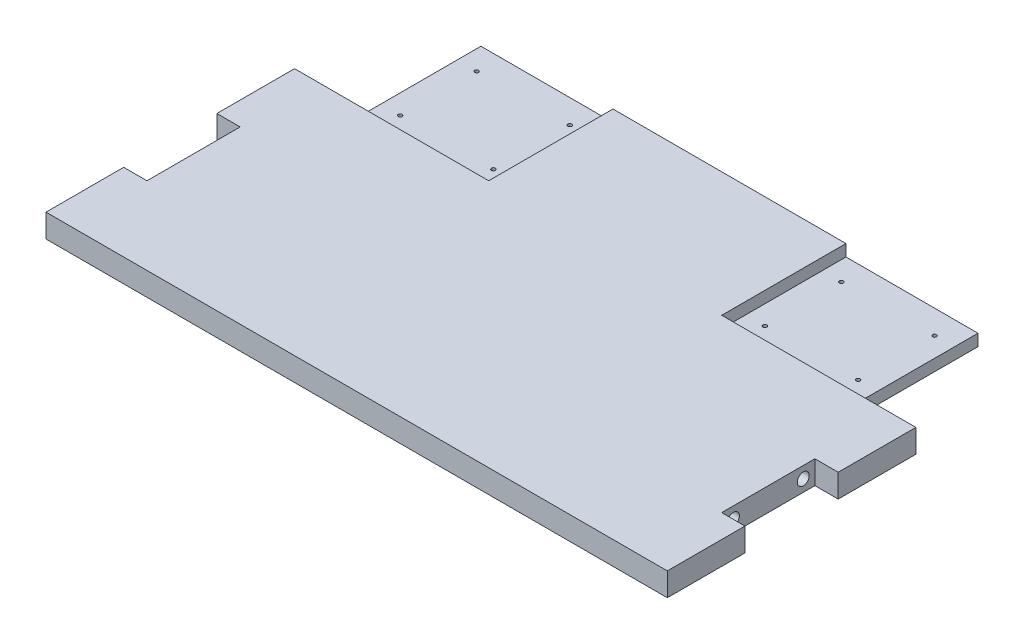
SolidWorks part; units mm, degrees
material "PE High Density"
ref_plane "Front Plane" through (0, 0, 0) normal (0, 0, 1) x (1, 0, 0)
ref_plane "Top Plane" through (0, 0, 0) normal (0, 1, 0) x (1, 0, 0)
ref_plane "Right Plane" through (0, 0, 0) normal (1, 0, 0) x (0, 0, -1)
sketch "Sketch1" plane through (0, 0, 0) normal (0, 1, 0) x (1, 0, 0)
  line L1 (-127, 127) -> (127, 127)
  line L2 (-127, 127) -> (-127, -127)
  line L3 (-127, -127) -> (127, -127)
  line L4 (127, 127) -> (127, -127)
  line L5 (-127, 127) -> (127, -127) construction
  line L6 (-127, -127) -> (127, 127) construction
  point P0 (0, 0)
  dimension "D1" = 254
  dimension "D2" = 254
extrude "Boss-Extrude1" add sketch "Sketch1" along normal blind 9.525
sketch "Sketch2" plane through (0, 9.525, 0) normal (0, 1, 0) x (1, 0, 0)
  line L0 (0, 0) -> (0, 151.7157) construction
  line L1 (-127, 127) -> (-101.6, 127)
  line L2 (-127, 127) -> (-127, 76.2)
  line L3 (-127, 76.2) -> (-101.6, 76.2)
  line L4 (-101.6, 127) -> (-101.6, 76.2)
  line L5 (127, 76.2) -> (101.6, 76.2)
  line L6 (127, 127) -> (127, 76.2)
  line L7 (127, 127) -> (101.6, 127)
  line L8 (101.6, 127) -> (101.6, 76.2)
  dimension "D1" = 50.8
  dimension "D2" = 25.4
extrude "Cut-Extrude1" cut sketch "Sketch2" against normal through all
sketch "Sketch4" plane through (0, 9.525, 0) normal (0, 1, 0) x (1, 0, 0)
  line L0 (0, 127) -> (0, 29.3179) construction
  line L1 (-101.6, 127) -> (-47.625, 127)
  line L2 (-101.6, 127) -> (-101.6, 76.2)
  line L3 (-101.6, 76.2) -> (-47.625, 76.2)
  line L4 (-47.625, 127) -> (-47.625, 76.2)
  line L5 (101.6, 127) -> (-101.6, 127) construction
  line L6 (101.6, 76.2) -> (47.625, 76.2)
  line L7 (101.6, 127) -> (101.6, 76.2)
  line L8 (101.6, 127) -> (47.625, 127)
  line L9 (47.625, 127) -> (47.625, 76.2)
  dimension "D1" = 53.975
  dimension "D2" = 50.8
extrude "Cut-Extrude2" cut sketch "Sketch4" against normal blind 4.7625
sketch "Sketch5" plane through (0, 4.7625, 0) normal (0, 1, 0) x (1, 0, 0)
  line L0 (-101.6, 101.6) -> (101.6, 101.6) construction
  line L1 (-101.6, 127) -> (-101.6, 76.2) construction
  line L2 (101.6, 76.2) -> (101.6, 127) construction
sketch "Sketch7" plane through (0, 9.525, 0) normal (0, 1, 0) x (1, 0, 0)
  line L0 (-127, 76.2) -> (-127, -25.4) construction
  line L1 (-127, 25.4) -> (-41.0029, 25.4) construction
  line L2 (0, 0) -> (0, -32.6591) construction
  line L3 (-127, 44.45) -> (-117.475, 44.45)
  line L4 (-127, 44.45) -> (-127, 6.35)
  line L5 (-127, 6.35) -> (-117.475, 6.35)
  line L6 (-117.475, 44.45) -> (-117.475, 6.35)
  line L7 (117.475, 44.45) -> (117.475, 6.35)
  line L8 (127, 6.35) -> (117.475, 6.35)
  line L9 (127, 44.45) -> (127, 6.35)
  line L10 (127, 44.45) -> (117.475, 44.45)
  line L11 (-127, 76.2) -> (-47.625, 76.2) construction
  point P10 (-117.475, 25.4)
  dimension "D1" = 38.1
  dimension "D2" = 9.525
  dimension "D3" = 31.75
extrude "Cut-Extrude4" cut sketch "Sketch7" against normal through all
hole_wizard "#10 (0.1935) Diameter Hole1" positions "Sketch11" profile "Sketch10" hole size "#10" standard "ANSI Inch"
sketch "Sketch11" plane through (117.475, 0, 0) normal (1, 0, 0) x (0, 0, -1)
  line L0 (44.45, 0) -> (44.45, 9.525) construction
  point P0 (11.1125, 4.7625)
  point P3 (39.6875, 4.7625)
  point P9 (44.45, 4.7625)
  dimension "D1" = 4.7625
  dimension "D2" = 28.575
sketch "Sketch10" plane through (117.475, 4.7625, -11.1125) normal (0, 1, 0) x (0, 0, -1)
  line L0 (0, 0) -> (0, 14.1766)
  line L1 (0, 14.1766) -> (2.4574, 12.7)
  line L2 (2.4574, 12.7) -> (2.4574, 0)
  line L5 (2.4574, 0) -> (0, 0)
  line L10 (0, 14.1766) -> (-2.4575, 12.7) construction
  line L11 (0, -6.35) -> (0, 107.95) construction
  dimension "Hole Dia." = 4.9149
  dimension "Hole Depth" = 12.7
  dimension "Drill Angle" = 118
hole_wizard "#10 (0.1935) Diameter Hole3" positions "Sketch15" profile "Sketch14" hole size "#10" standard "ANSI Inch"
sketch "Sketch15" plane through (-117.475, 0, 0) normal (-1, 0, 0) x (0, 0, 1)
  line L0 (-6.35, 0) -> (-6.35, 9.525) construction
  point P0 (-39.6875, 4.7625)
  point P3 (-11.1125, 4.7625)
  point P8 (-6.35, 4.7625)
  dimension "D1" = 4.7625
  dimension "D2" = 28.575
sketch "Sketch14" plane through (-117.475, 4.7625, -39.6875) normal (0, 1, 0) x (0, 0, 1)
  line L0 (0, 0) -> (0, 14.1766)
  line L1 (0, 14.1766) -> (2.4574, 12.7)
  line L2 (2.4574, 12.7) -> (2.4574, 0)
  line L5 (2.4574, 0) -> (0, 0)
  line L10 (0, 14.1766) -> (-2.4574, 12.7) construction
  line L11 (0, -6.35) -> (0, 107.95) construction
  dimension "Hole Dia." = 4.9149
  dimension "Hole Depth" = 12.7
  dimension "Drill Angle" = 118
sketch "Sketch16" plane through (0, 4.7625, 0) normal (0, 1, 0) x (1, 0, 0)
  line L0 (0, 0) -> (0, 45.1686) construction
  circle A0 centre (93.599, 117.221) radius 1.651 construction
  circle A1 centre (55.499, 117.221) radius 1.651 construction
  circle A2 centre (55.499, 85.979) radius 1.651 construction
  circle A3 centre (93.599, 85.979) radius 1.651 construction
  circle A4 centre (-55.499, 85.979) radius 1.651 construction
  circle A5 centre (-93.599, 85.979) radius 1.651 construction
  circle A6 centre (-93.599, 117.221) radius 1.651 construction
  circle A7 centre (-55.499, 117.221) radius 1.651 construction
  circle A8 centre (93.599, 117.221) radius 0.7937
  circle A9 centre (55.499, 117.221) radius 0.7937
  circle A10 centre (55.499, 85.979) radius 0.7937
  circle A11 centre (93.599, 85.979) radius 0.7937
  circle A12 centre (-93.599, 85.979) radius 1.651 construction
  circle A13 centre (-55.499, 85.979) radius 1.651 construction
  circle A14 centre (-55.499, 117.221) radius 1.651 construction
  circle A15 centre (-93.599, 117.221) radius 1.651 construction
  circle A16 centre (-93.599, 85.979) radius 0.7938
  circle A17 centre (-55.499, 85.979) radius 0.7938
  circle A18 centre (-55.499, 117.221) radius 0.7938
  circle A19 centre (-93.599, 117.221) radius 0.7938
  dimension "D1" = 1.5875
extrude "Cut-Extrude7" cut sketch "Sketch16" against normal through all
sketch "Sketch17" plane through (0, 9.525, 0) normal (0, 1, 0) x (1, 0, 0)
  line L0 (127, -127) -> (127, 6.35) construction
  line L1 (-127, -127) -> (127, -127)
  line L2 (-127, -127) -> (-127, -25.4)
  line L3 (-127, -25.4) -> (127, -25.4)
  line L4 (127, -127) -> (127, -25.4)
  dimension "D1" = 101.6
extrude "Cut-Extrude8" cut sketch "Sketch17" against normal through all
